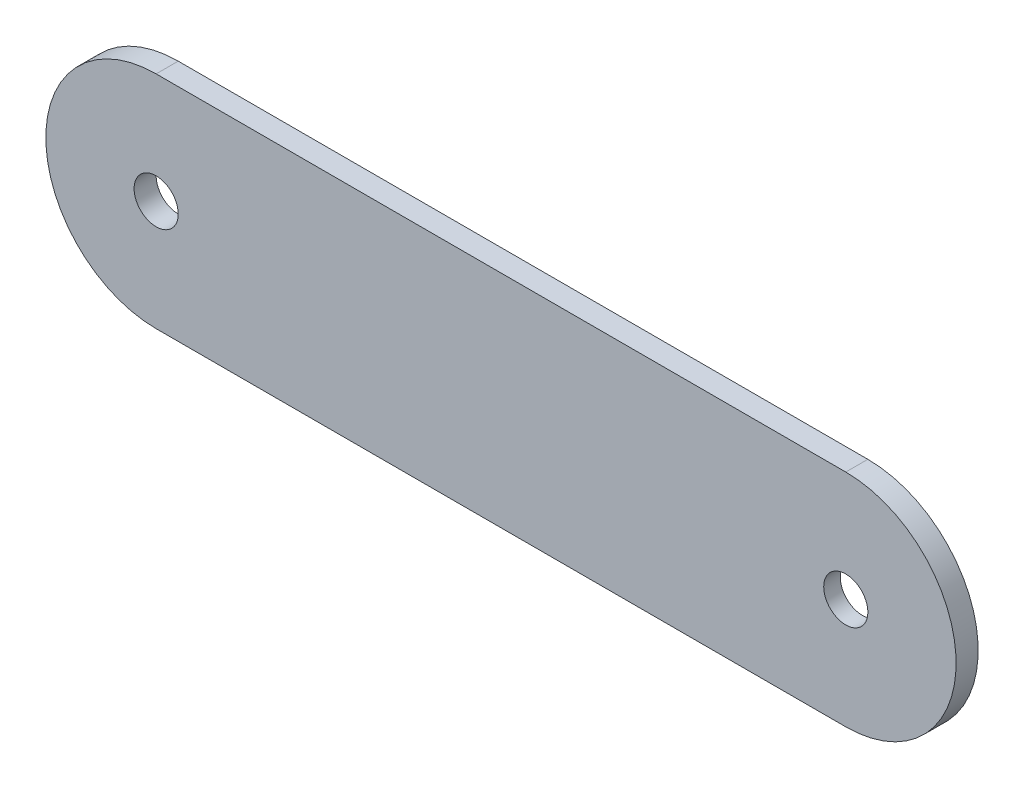
SolidWorks part; units mm, degrees
ref_plane "Front Plane" through (0, 0, 0) normal (0, 0, 1) x (1, 0, 0)
ref_plane "Top Plane" through (0, 0, 0) normal (0, 1, 0) x (1, 0, 0)
ref_plane "Right Plane" through (0, 0, 0) normal (1, 0, 0) x (0, 0, -1)
sketch "Sketch1" plane through (0, 0, 0) normal (0, 0, 1) x (1, 0, 0)
  line L0 (474.7471, 99.4239) -> (-150.2529, 99.4239)
  line L1 (474.7471, -100.5761) -> (-150.2529, -100.5761)
  line L2 (474.7471, 94.4239) -> (-150.2529, 94.4239) construction
  line L3 (474.7471, -95.5761) -> (-150.2529, -95.5761) construction
  arc A0 (474.7471, -100.5761) -> (474.7471, 99.4239) centre (474.7471, -0.5761) ccw
  arc A2 (-150.2529, 99.4239) -> (-150.2529, -100.5761) centre (-150.2529, -0.5761) ccw
  arc A3 (-150.2529, 94.4239) -> (-150.2529, -95.5761) centre (-150.2529, -0.5761) ccw construction
  arc A4 (474.7471, -95.5761) -> (474.7471, 94.4239) centre (474.7471, -0.5761) ccw construction
  circle A5 centre (-150.2529, -0.5761) radius 30 construction
  circle A6 centre (-150.2529, -0.5761) radius 20
  circle A7 centre (474.7471, -0.5761) radius 20
  circle A8 centre (474.7471, -0.5761) radius 30 construction
  dimension "D1" = 100
  dimension "D2" = 625
  dimension "D3" = 100
  dimension "D5" = 60
  dimension "D6" = 40
  dimension "D4" = 5
extrude "Boss-Extrude2" add sketch "Sketch1" along normal blind 20
sketch "Sketch8" plane through (0, 0, 0) normal (0, 0, 1) x (1, 0, 0)
  line L6 (474.7471, 99.4239) -> (-150.2529, 99.4239) construction
  line L7 (-150.2529, -100.5761) -> (474.7471, -100.5761) construction
  line L8 (-150.2529, -95.5761) -> (474.7471, -95.5761)
  line L9 (474.7471, 94.4239) -> (-150.2529, 94.4239)
  line L10 (-150.2529, -95.5761) -> (474.7471, -95.5761)
  line L11 (474.7471, 94.4239) -> (-150.2529, 94.4239)
  arc A6 (-150.2529, 94.4239) -> (-150.2529, -95.5761) centre (-150.2529, -0.5761) ccw
  arc A7 (474.7471, -95.5761) -> (474.7471, 94.4239) centre (474.7471, -0.5761) ccw
  arc A8 (-150.2529, 94.4239) -> (-150.2529, -95.5761) centre (-150.2529, -0.5761) ccw
  arc A9 (474.7471, -95.5761) -> (474.7471, 94.4239) centre (474.7471, -0.5761) ccw
  circle A15 centre (474.7471, -0.5761) radius 25
  circle A16 centre (474.7471, -0.5761) radius 25
  circle A17 centre (474.7471, -0.5761) radius 20 construction
  circle A18 centre (-150.2529, -0.5761) radius 25
  circle A19 centre (-150.2529, -0.5761) radius 25
  circle A20 centre (474.7471, -0.5761) radius 20 construction
  circle A21 centre (-150.2529, -0.5761) radius 20 construction
  circle A22 centre (-150.2529, -0.5761) radius 20 construction
  arc A23 (-150.2529, 99.4239) -> (-150.2529, -100.5761) centre (-150.2529, -0.5761) ccw construction
  arc A24 (474.7471, -100.5761) -> (474.7471, 99.4239) centre (474.7471, -0.5761) ccw construction
  dimension "D1" = 5
  dimension "D2" = 5
  dimension "D3" = 5
  dimension "D4" = 5
extrude "Cut-Extrude6" cut sketch "Sketch8" along normal blind 5 contours A8 L10 A9 L11 | A19
